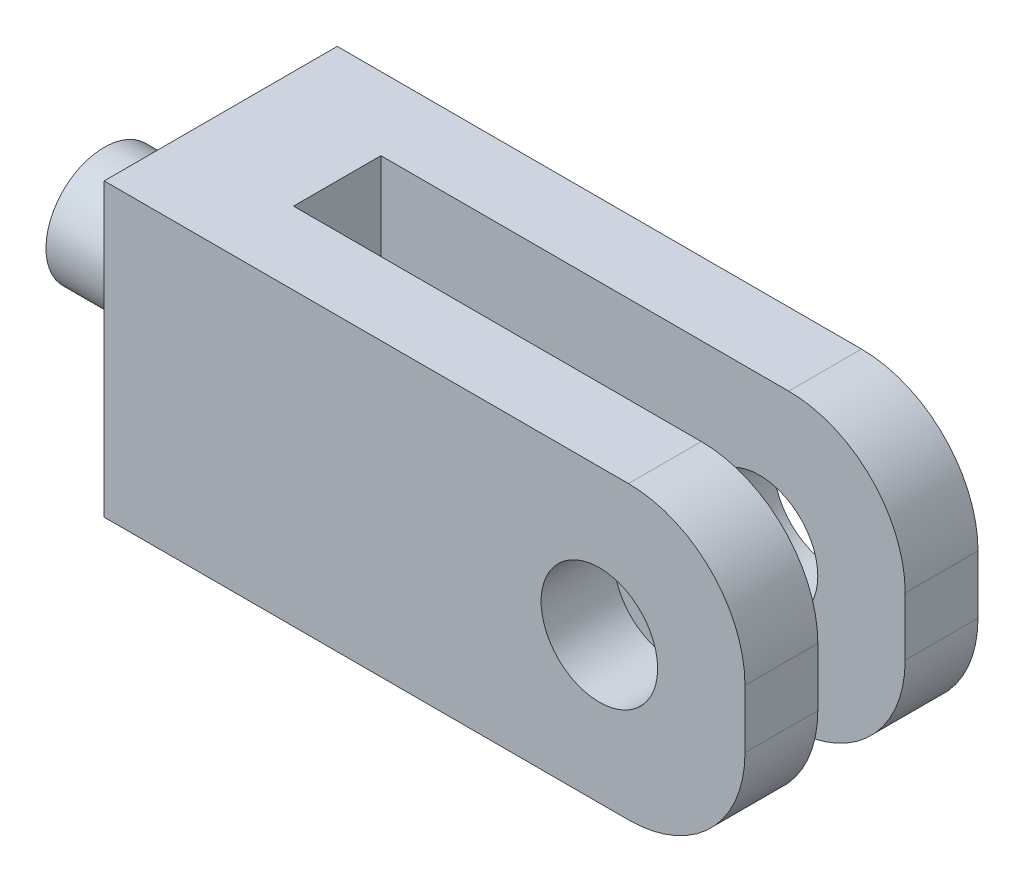
SolidWorks part; units mm, degrees
ref_plane "Front Plane" through (0, 0, 0) normal (0, 0, 1) x (1, 0, 0)
ref_plane "Top Plane" through (0, 0, 0) normal (0, 1, 0) x (1, 0, 0)
ref_plane "Right Plane" through (0, 0, 0) normal (1, 0, 0) x (0, 0, -1)
sketch "Sketch1" plane through (0, 0, 0) normal (0, 0, 1) x (1, 0, 0)
  line L1 (-55, 25) -> (55, 25)
  line L2 (-55, 25) -> (-55, -25)
  line L3 (-55, -25) -> (55, -25)
  line L4 (55, 25) -> (55, -25)
  line L5 (-55, 25) -> (55, -25) construction
  line L6 (-55, -25) -> (55, 25) construction
  point P0 (0, 0)
  dimension "D1" = 110
  dimension "D2" = 50
extrude "Boss-Extrude1" add sketch "Sketch1" along normal blind 40
sketch "Sketch2" plane through (55, 0, 0) normal (1, 0, 0) x (0, 0, -1)
  line L0 (-40, 25) -> (0, 25) construction
  line L5 (-12.5, -25) -> (-27.5, -25)
  line L6 (-12.5, -25) -> (-12.5, 25)
  line L7 (-12.5, 25) -> (-27.5, 25)
  line L8 (-27.5, -25) -> (-27.5, 25)
  line L9 (-12.5, -25) -> (-27.5, 25) construction
  line L10 (-12.5, 25) -> (-27.5, -25) construction
  point P0 (-20, 0)
  dimension "D1" = 15
  dimension "D2" = 20
extrude "Cut-Extrude1" cut sketch "Sketch2" against normal blind 90
fillet "Fillet1" radius 20 4 edges at (55, -25, 6.25) (55, 25, 6.25) (55, -25, 33.75) (55, 25, 33.75)
sketch "Sketch3" plane through (0, 0, 40) normal (0, 0, 1) x (1, 0, 0)
  circle A0 centre (30, 0) radius 10
  dimension "D1" = 20
  dimension "D2" = 30
extrude "Cut-Extrude2" cut sketch "Sketch3" against normal through all
sketch "Sketch4" plane through (-55, 0, 0) normal (-1, 0, 0) x (0, 0, 1)
  line L0 (40, 25) -> (0, -25) construction
  circle A0 centre (20, 0) radius 10
  dimension "D1" = 20
extrude "Boss-Extrude2" add sketch "Sketch4" along normal blind 20
